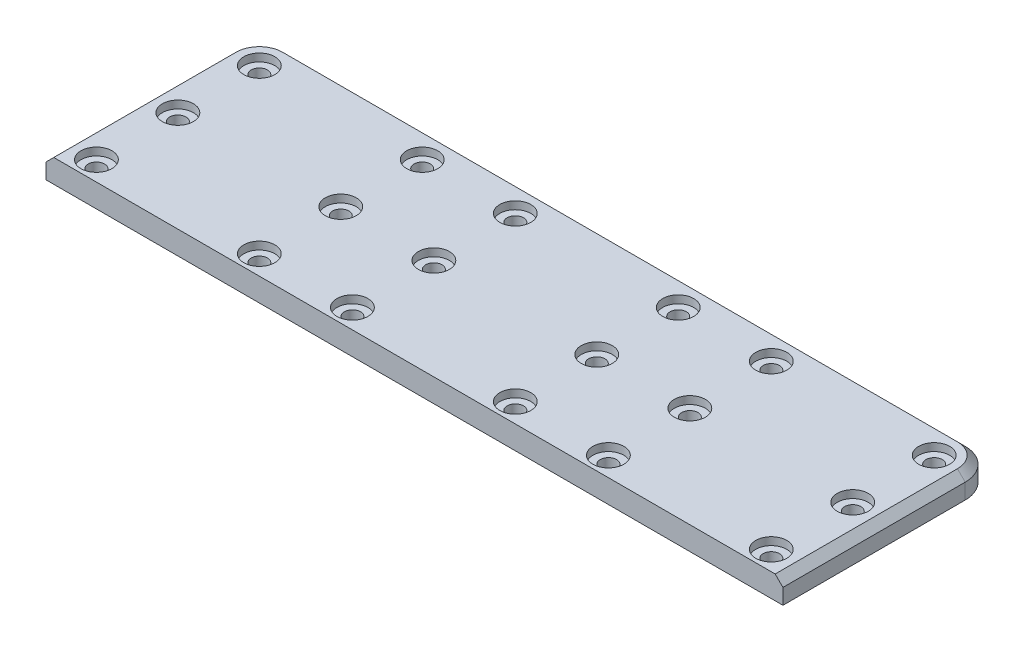
SolidWorks part; units mm, degrees
material "ABS"
ref_plane "正面" through (0, 0, 0) normal (0, 0, 1) x (1, 0, 0)
ref_plane "平面" through (0, 0, 0) normal (0, 1, 0) x (1, 0, 0)
ref_plane "右側面" through (0, 0, 0) normal (1, 0, 0) x (0, 0, -1)
sketch "ｽｹｯﾁ1" plane through (0, 0, 0) normal (0, 1, 0) x (1, 0, 0)
  line L0 (-10.05, 0) -> (-39, 0)
  line L1 (-39, 0) -> (-47.5, 8.5)
  line L2 (-47.5, 8.5) -> (-47.5, 58)
  line L3 (-47.5, 58) -> (47.5, 58)
  line L4 (47.5, 58) -> (47.5, 8.5)
  line L5 (47.5, 8.5) -> (39, 0)
  line L6 (39, 0) -> (10.05, 0)
  line L7 (-10.05, 0) -> (0, 0) construction
  line L8 (0, 0) -> (10.05, 0) construction
  arc A0 (10.05, 0) -> (-10.05, 0) centre (0, 0) ccw
  dimension "D1" = 20.1
  dimension "D2" = 95
  dimension "D3" = 58
  dimension "D4" = 78
extrude "ﾎﾞｽ - 押し出し1" add sketch "ｽｹｯﾁ1" along normal blind 3
hole_wizard "M2 なべ頭ねじ用座ぐり穴1" positions "ｽｹｯﾁ2" profile "ｽｹｯﾁ3" counterbore size "M2" standard "ISO"
sketch "ｽｹｯﾁ2" plane through (0, 3, 0) normal (0, 1, 0) x (1, 0, 0)
  line L0 (-43.5, 54) -> (-22.5, 54) construction
  line L2 (47.5, 58) -> (-47.5, 58) construction
  line L3 (-47.5, 58) -> (-47.5, 8.5) construction
  point P0 (-43.5, 54)
  point P2 (-22.5, 54)
  dimension "D1" = 4
  dimension "D2" = 4
  dimension "D3" = 21
sketch "ｽｹｯﾁ3" plane through (-43.5, 3, -54) normal (1, 0, 0) x (0, 0, 1)
  line L0 (0, 0) -> (0, 4.6309)
  line L1 (0, 4.6309) -> (1.05, 4)
  line L2 (1.05, 4) -> (1.05, 1)
  line L3 (1.05, 1) -> (2, 1)
  line L4 (2, 1) -> (2, 0)
  line L5 (2, 0) -> (0, 0)
  line L10 (0, 4.6309) -> (-1.05, 4) construction
  line L11 (0, -6.35) -> (0, 107.95) construction
  dimension "穴の直径" = 2.1
  dimension "穴の深さ" = 4
  dimension "座ぐり穴の直径" = 4
  dimension "座ぐり穴の深さ" = 1
  dimension "ﾄﾞﾘﾙ角度" = 118
pattern_linear "直線ﾊﾟﾀｰﾝ1" count 3 spacing 33 along (1, 0, 0) of "M2 なべ頭ねじ用座ぐり穴1"
pattern_linear "直線ﾊﾟﾀｰﾝ2" count 3 spacing 10.5 along (0, 0, 1) of "M2 なべ頭ねじ用座ぐり穴1", "直線ﾊﾟﾀｰﾝ1"
pattern_linear "直線ﾊﾟﾀｰﾝ3" count 2 spacing 31.5 along (0, 0, 1) of "M2 なべ頭ねじ用座ぐり穴1"
hole_wizard "M2 ねじ穴1" positions "ｽｹｯﾁ4" profile "ｽｹｯﾁ5" tap size "M2" standard "ISO"
sketch "ｽｹｯﾁ4" plane through (0, 3, 0) normal (0, 1, 0) x (1, 0, 0)
  line L0 (-22.5, 10.5) -> (-22.5, 22.5) construction
  line L1 (-22.5, 22.5) -> (-10.5, 22.5) construction
  line L2 (-10.5, 22.5) -> (-10.5, 33) construction
  line L4 (-39, 0) -> (-10.05, 0) construction
  point P0 (-10.5, 22.5)
  point P2 (-22.5, 10.5)
  dimension "D1" = 10.5
sketch "ｽｹｯﾁ5" plane through (-10.5, 3, -22.5) normal (1, 0, 0) x (0, 0, 1)
  line L0 (0, 0) -> (0, 6.4807)
  line L1 (0, 6.4807) -> (0.8, 6)
  line L2 (0.8, 6) -> (0.8, 0)
  line L5 (0.8, 0) -> (0, 0)
  line L10 (0, 6.4807) -> (-0.8, 6) construction
  line L11 (0, -6.35) -> (0, 107.95) construction
  dimension "ねじ下穴ﾄﾞﾘﾙ直径" = 1.6
  dimension "ねじ下穴ﾄﾞﾘﾙの深さ" = 6
  dimension "ﾄﾞﾘﾙ角度" = 118
cosmetic thread "穴のねじ山1" parameters "D1"=4, "D2"=2
cosmetic thread "穴のねじ山2" parameters "D1"=4, "D2"=2
hole_wizard "M2 なべ頭ねじ用座ぐり穴2" positions "ｽｹｯﾁ6" profile "ｽｹｯﾁ7" counterbore size "M2" standard "ISO"
sketch "ｽｹｯﾁ6" plane through (0, 3, 0) normal (0, 1, 0) x (1, 0, 0)
  line L0 (-43.5, 22.5) -> (-43.5, 12) construction
  line L3 (-43.5, 33) -> (-43.5, 22.5) construction
  point P0 (-43.5, 12)
sketch "ｽｹｯﾁ7" plane through (-43.5, 3, -12) normal (1, 0, 0) x (0, 0, 1)
  line L0 (0, 0) -> (0, 6.6309)
  line L1 (0, 6.6309) -> (1.05, 6)
  line L2 (1.05, 6) -> (1.05, 1)
  line L3 (1.05, 1) -> (2, 1)
  line L4 (2, 1) -> (2, 0)
  line L5 (2, 0) -> (0, 0)
  line L10 (0, 6.6309) -> (-1.05, 6) construction
  line L11 (0, -6.35) -> (0, 107.95) construction
  dimension "穴の直径" = 2.1
  dimension "穴の深さ" = 6
  dimension "座ぐり穴の直径" = 4
  dimension "座ぐり穴の深さ" = 1
  dimension "ﾄﾞﾘﾙ角度" = 118
mirror "ﾐﾗｰ1" about plane through (0, 0, 0) normal (1, 0, 0) of "M2 なべ頭ねじ用座ぐり穴2", "M2 ねじ穴1", "直線ﾊﾟﾀｰﾝ3"
cosmetic thread "穴のねじ山3" parameters "D1"=4, "D2"=2
cosmetic thread "穴のねじ山4" parameters "D1"=4, "D2"=2
sketch "ｽｹｯﾁ8" plane through (0, 3, 0) normal (0, 1, 0) x (1, 0, 0)
  circle A0 centre (0, 0) radius 17
  dimension "D1" = 34
extrude "ｶｯﾄ - 押し出し1" cut sketch "ｽｹｯﾁ8" against normal blind 1
sketch "ｽｹｯﾁ9" plane through (0, 2, 0) normal (0, 1, 0) x (1, 0, 0)
  line L0 (-9.8995, 9.8995) -> (0, 0) construction
  line L2 (-17, 0) -> (-10.05, 0) construction
  circle A0 centre (-9.8995, 9.8995) radius 2.025
  dimension "D1" = 4.05
  dimension "D2" = 45
  dimension "D3" = 14
extrude "ｶｯﾄ - 押し出し2" cut sketch "ｽｹｯﾁ9" against normal through all
pattern_circular "円形ﾊﾟﾀｰﾝ1" count 2 every 90 about axis through (0, 3, 0) along (0, -1, 0) of "ｶｯﾄ - 押し出し2"
fillet "ﾌｨﾚｯﾄ1" radius 4 6 edges at (-47.5, 1.5, -8.5) (-39, 1.5, 0) (39, 1.5, 0) (47.5, 1.5, -8.5) (47.5, 1.5, -58) (-47.5, 1.5, -58)
chamfer "面取り1" distance 1 angle 45 14 edges at (0, 3, -17) (27.1716, 3, 0) (38.8739, 3, -0.3045) (43.25, 3, -4.25) (47.1955, 3, -8.6261) (47.5, 3, -32.0784) (-27.1716, 3, 0) (46.3284, 3, -56.8284) (-38.8739, 3, -0.3045) (0, 3, -58) (-43.25, 3, -4.25) (-46.3284, 3, -56.8284) (-47.1955, 3, -8.6261) (-47.5, 3, -32.0784)
sketch "ｽｹｯﾁ10" plane through (0, 3, 0) normal (0, 1, 0) x (1, 0, 0)
  line L0 (0, -1.65) -> (0, 1.65) construction
  line L1 (-47.5, 30.5) -> (47.5, 30.5)
  line L2 (-47.5, 30.5) -> (-47.5, 0)
  line L3 (-47.5, 0) -> (47.5, 0)
  line L4 (47.5, 30.5) -> (47.5, 0)
  line L5 (-47.5, 30.5) -> (47.5, 0) construction
  line L6 (-47.5, 0) -> (47.5, 30.5) construction
  line L7 (-17, 0) -> (-37.3431, 0) construction
  line L8 (-47.5, 10.1569) -> (-47.5, 54) construction
  circle A0 centre (-43.5, 33) radius 1.05 construction
  point P4 (0, 15.25)
  dimension "D2" = 2.5
  dimension "D1" = 0
extrude "ｶｯﾄ - 押し出し3" cut sketch "ｽｹｯﾁ10" against normal up to next
